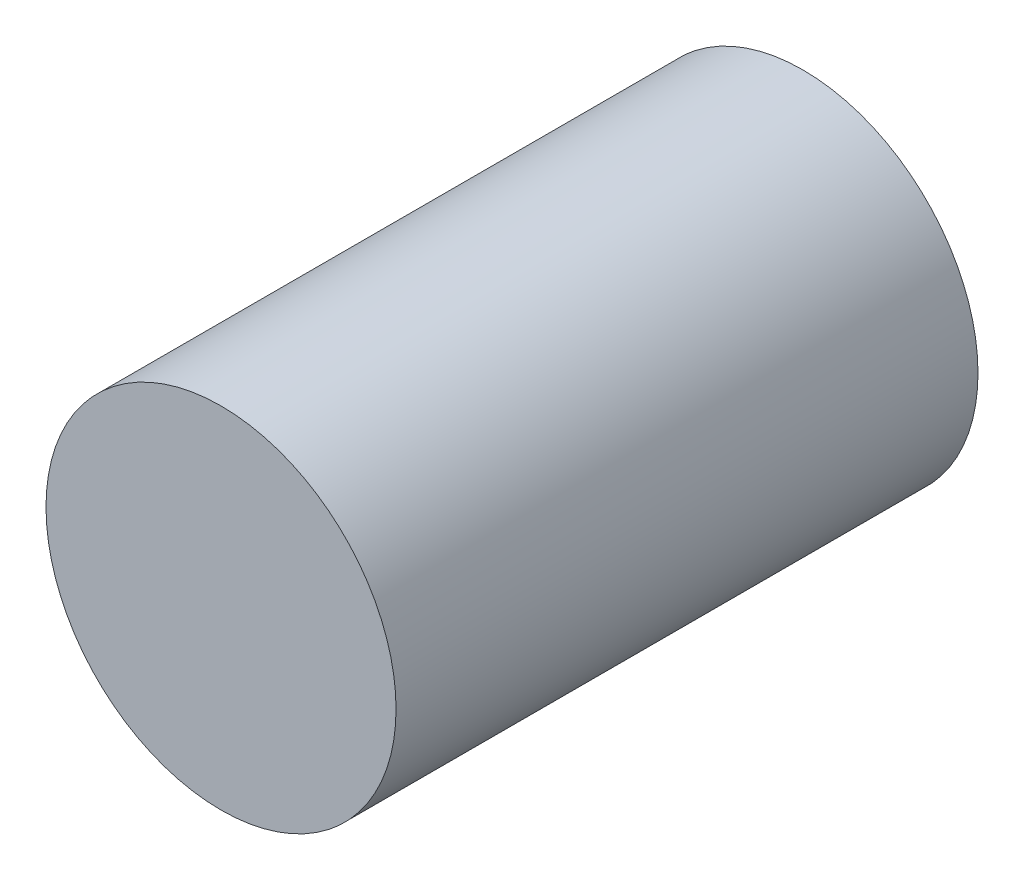
SolidWorks part; units mm, degrees
material "AISI Type A2 Tool Steel"
ref_plane "Front Plane" through (0, 0, 0) normal (0, 0, 1) x (1, 0, 0)
ref_plane "Top Plane" through (0, 0, 0) normal (0, 1, 0) x (1, 0, 0)
ref_plane "Right Plane" through (0, 0, 0) normal (1, 0, 0) x (0, 0, -1)
sketch "Sketch1" plane through (0, 0, 0) normal (0, 0, 1) x (1, 0, 0)
  circle A0 centre (0, 0) radius 6.015
  dimension "D1" = 12.03
extrude "Boss-Extrude3" add sketch "Sketch1" along normal mid plane 20 contours A0
